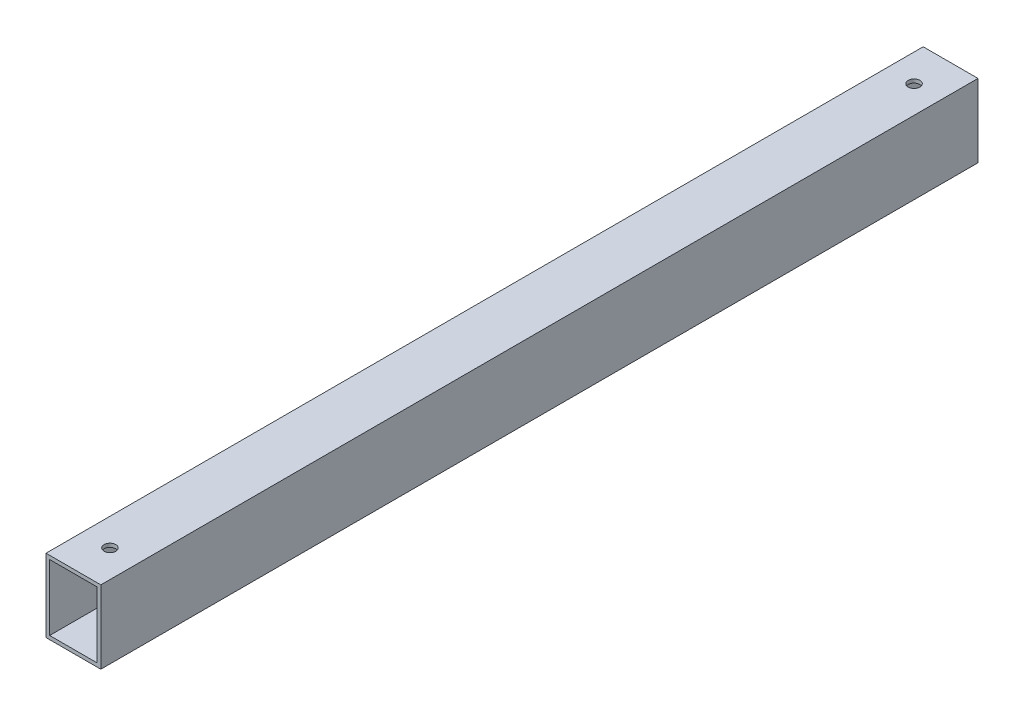
SolidWorks part; units mm, degrees
material "1060 合金"
ref_plane "前视基准面" through (0, 0, 0) normal (0, 0, 1) x (1, 0, 0)
ref_plane "上视基准面" through (0, 0, 0) normal (0, 1, 0) x (1, 0, 0)
ref_plane "右视基准面" through (0, 0, 0) normal (1, 0, 0) x (0, 0, -1)
other "Configuration Table"
sketch "草图1" plane through (0, 0, 0) normal (0, 0, 1) x (1, 0, 0)
  line L1 (0, 0) -> (15, 0)
  line L2 (0, 0) -> (0, -20)
  line L3 (0, -20) -> (15, -20)
  line L4 (15, 0) -> (15, -20)
  dimension "D1" = 20
  dimension "D2" = 15
extrude "拉伸-薄壁1" add sketch "草图1" along normal blind 240 thin
sketch "草图2" plane through (0, -20, 0) normal (0, -1, 0) x (1, 0, 0)
  circle A1 centre (7.5, 825) radius 2.6
  circle A2 centre (7.5, 825) radius 2.6
  dimension "D1" = 0
extrude "切除-拉伸1" [suppressed] cut sketch "草图2" against normal up to next
sketch "草图3" plane through (0, 0, 0) normal (0, 1, 0) x (1, 0, 0)
  line L0 (15, -240) -> (15, 0) construction
  line L1 (15, 0) -> (0, 0) construction
  circle A0 centre (7.5, -10) radius 1.6
  circle A1 centre (7.5, -230) radius 1.6
  dimension "D3" = 3.2
  dimension "D1" = 7.5
  dimension "D2" = 10
  dimension "D4" = 2
extrude "切除-拉伸2" cut sketch "草图3" against normal through all
